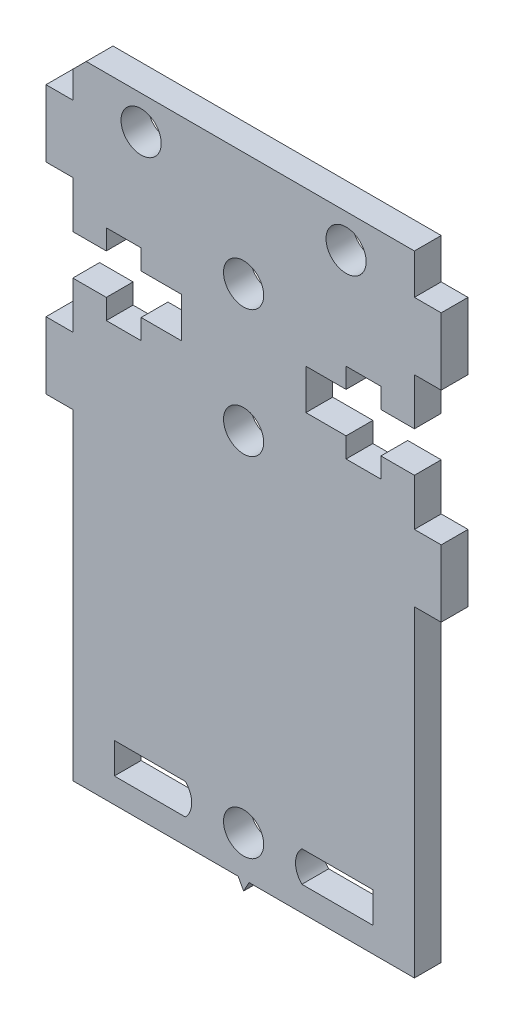
SolidWorks part; units mm, degrees
other "标注1"
sketch "草图6" plane through (-10.9329, 12.799, 2.5) normal (-0.1258, 0.0395, 0.9913) x (0.9919, 0.0245, 0.1249)
ref_plane "前视基准面" through (0, 0, 0) normal (0, 0, 1) x (1, 0, 0)
ref_plane "上视基准面" through (0, 0, 0) normal (0, 1, 0) x (1, 0, 0)
ref_plane "右视基准面" through (0, 0, 0) normal (1, 0, 0) x (0, 0, -1)
sketch "草图1" plane through (0, 0, 0) normal (0, 0, 1) x (1, 0, 0)
  line L1 (-8.9329, -10.701) -> (-10.9329, -10.701)
  line L2 (-10.9329, -10.701) -> (-10.9329, -5.701)
  line L26 (-10.9329, -5.701) -> (-8.9329, -5.701)
  line L33 (-8.9329, 4.299) -> (-10.9329, 4.299)
  line L34 (-10.9329, 4.299) -> (-10.9329, 9.299)
  line L35 (-10.9329, 9.299) -> (-8.9329, 9.299)
  line L36 (-8.9329, 9.299) -> (-8.9329, 11.299)
  line L37 (16.5671, 9.299) -> (16.5671, 12.299)
  line L38 (18.5671, 9.299) -> (16.5671, 9.299)
  line L39 (18.5671, 4.299) -> (18.5671, 9.299)
  line L40 (16.5671, 4.299) -> (18.5671, 4.299)
  line L42 (18.5671, -5.701) -> (16.5671, -5.701)
  line L48 (18.5671, -10.701) -> (18.5671, -5.701)
  line L49 (16.5671, -10.701) -> (18.5671, -10.701)
  line L55 (13.3171, -30.701) -> (8.3171, -30.701) construction
  line L57 (13.4671, -32.8428) -> (8.1671, -32.8428)
  line L58 (13.4671, -30.5428) -> (13.4671, -32.8428)
  line L63 (-5.6829, -30.701) -> (-0.6829, -30.701) construction
  line L64 (-5.6829, -30.701) -> (-5.6829, -30.5428)
  line L65 (-5.6829, -30.5428) -> (-5.8329, -30.5428)
  line L66 (13.4671, -30.5428) -> (8.1671, -30.5428)
  line L67 (-5.8329, -30.5428) -> (-0.5329, -30.5428)
  line L68 (-5.8329, -30.5428) -> (-5.8329, -32.8428)
  line L69 (-5.8329, -32.8428) -> (-0.5329, -32.8428)
  line L71 (13.3171, -30.5428) -> (13.4671, -30.5428)
  line L72 (13.3171, -30.701) -> (13.3171, -30.5428)
  line L76 (3.8171, -35.4558) -> (4.223, -34.701)
  line L77 (4.223, -34.701) -> (16.5671, -34.701)
  line L81 (3.8171, -35.4558) -> (3.4111, -34.701)
  line L82 (-8.9329, -34.701) -> (3.4111, -34.701)
  line L83 (-6.4329, -2.201) -> (-6.4329, -3.701)
  line L84 (-0.8329, 0.799) -> (-0.8329, -2.201)
  line L86 (-6.4329, 0.799) -> (-6.4329, 2.299)
  line L87 (-8.9329, 0.799) -> (-6.4329, 0.799)
  line L88 (-6.4329, -3.701) -> (-3.8329, -3.701)
  line L89 (-3.8329, -3.701) -> (-3.8329, -2.201)
  line L90 (-3.8329, -2.201) -> (-0.8329, -2.201)
  line L91 (-3.8329, 0.799) -> (-0.8329, 0.799)
  line L92 (-3.8329, 2.299) -> (-3.8329, 0.799)
  line L93 (-6.4329, 2.299) -> (-3.8329, 2.299)
  line L94 (-6.4329, -2.201) -> (-8.9329, -2.201)
  line L98 (14.0671, 2.299) -> (11.4671, 2.299)
  line L99 (11.4671, 2.299) -> (11.4671, 0.799)
  line L100 (11.4671, 0.799) -> (8.4671, 0.799)
  line L101 (11.4671, -2.201) -> (8.4671, -2.201)
  line L102 (11.4671, -3.701) -> (11.4671, -2.201)
  line L103 (14.0671, -3.701) -> (11.4671, -3.701)
  line L104 (14.0671, 0.799) -> (14.0671, 2.299)
  line L105 (8.4671, 0.799) -> (8.4671, -2.201)
  line L106 (14.0671, -2.201) -> (14.0671, -3.701)
  line L107 (14.0671, 0.799) -> (16.5671, 0.799)
  line L109 (14.0671, -2.201) -> (16.5671, -2.201)
  line L115 (16.5671, 12.299) -> (-7.9329, 12.299)
  line L116 (-7.9329, 12.299) -> (-8.9329, 11.299)
  line L117 (-8.9329, -5.701) -> (-8.9329, -2.201)
  line L118 (-3.8329, 12.299) -> (-3.8329, 9.799) construction
  line L119 (16.5671, -2.201) -> (16.5671, -5.701)
  line L120 (-8.9329, 4.299) -> (-8.9329, 0.799)
  line L121 (16.5671, 4.299) -> (16.5671, 0.799)
  line L122 (-8.9329, -34.701) -> (-8.9329, -10.701)
  line L123 (16.5671, -10.701) -> (16.5671, -34.701)
  circle A6 centre (3.8171, -5.701) radius 1.5
  circle A7 centre (3.8171, 3.799) radius 1.5
  arc A8 (-0.5329, -30.5428) -> (-0.5329, -32.8428) centre (-1.6829, -31.6928) cw
  arc A9 (8.1671, -30.5428) -> (8.1671, -32.8428) centre (9.3171, -31.6928) ccw
  circle A10 centre (3.8171, -31.6928) radius 1.5
  circle A11 centre (-3.8329, 9.799) radius 1.5
  circle A12 centre (11.4671, 9.799) radius 1.5
  point P13 (-8.9329, 12.299)
extrude "凸台-拉伸1" add sketch "草图1" along normal blind 2
sketch "草图2" plane through (-8.9329, 0, 0) normal (-1, 0, 0) x (0, 0, 1)
  line L0 (1, 0.799) -> (1, -2.201)
  line L1 (2, 0.799) -> (0, 0.799) construction
  line L2 (2, -2.201) -> (0, -2.201) construction
  circle A0 centre (1, -0.701) radius 1.5
sketch "草图3" plane through (16.5671, 0, 0) normal (1, 0, 0) x (0, 0, -1)
  line L0 (-1, 0.799) -> (-1, -2.201)
  line L1 (-2, 0.799) -> (0, 0.799) construction
  line L2 (-2, -2.201) -> (0, -2.201) construction
  circle A0 centre (-1, -0.701) radius 1.5
sketch "草图5" plane through (16.5671, 0, 0) normal (1, 0, 0) x (0, 0, -1)
  line L0 (-1, -34.701) -> (-1, -35.4558)
  line L1 (-2, -34.701) -> (0, -34.701) construction
  line L2 (-2, -35.4558) -> (0, -35.4558) construction
  line L3 (-1, -35.4558) -> (0, -34.701)
  line L4 (0, -34.701) -> (0, -35.4558)
  line L5 (0, -35.4558) -> (-1, -35.4558)
  line L6 (-2, -35.4558) -> (-2, -34.701)
  line L7 (-2, -34.701) -> (-1, -35.4558)
  line L8 (-2, -35.4558) -> (-1, -35.4558)
extrude "切除-拉伸2" [suppressed] cut sketch "草图5" against normal blind 20 contours L6 L8 L7 | L5 L4 L3
